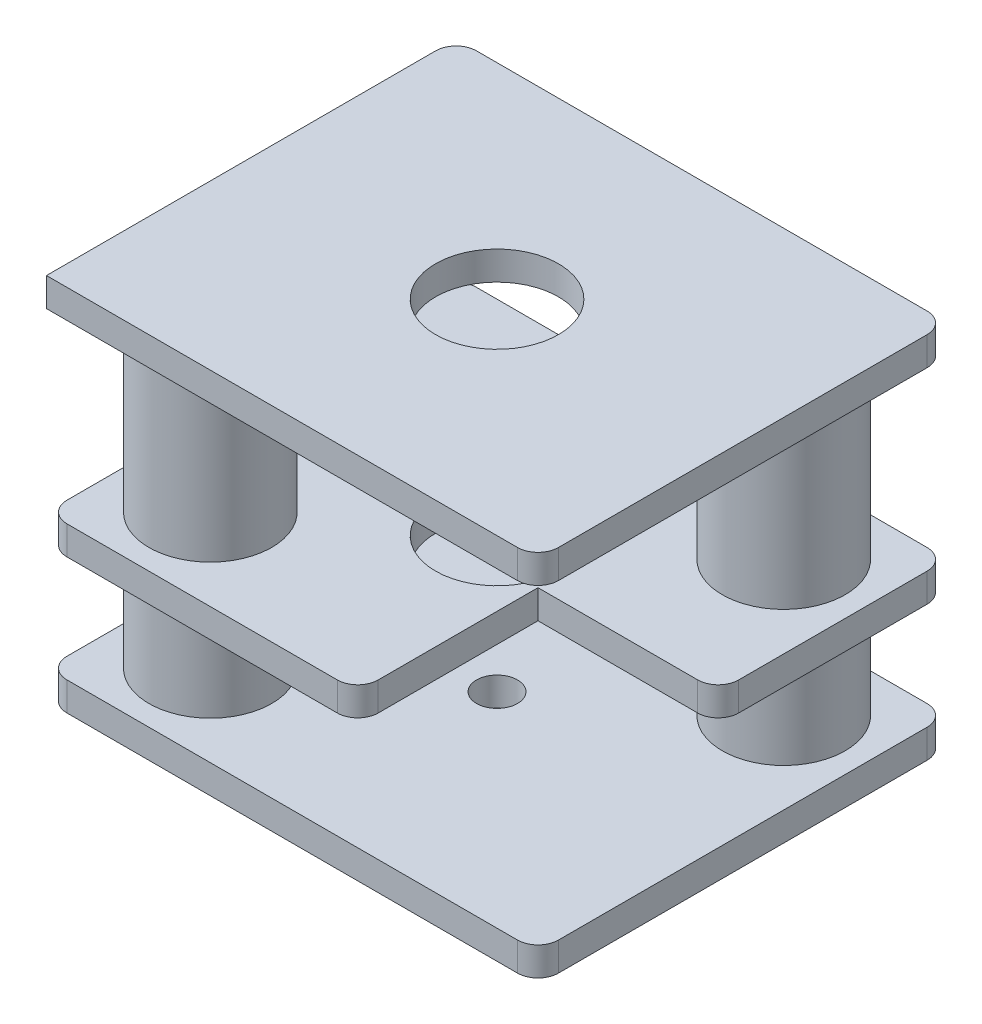
SolidWorks part; units mm, degrees
ref_plane "Alzado" through (0, 0, 0) normal (0, 0, 1) x (1, 0, 0)
ref_plane "Planta" through (0, 0, 0) normal (0, 1, 0) x (1, 0, 0)
ref_plane "Vista lateral" through (0, 0, 0) normal (1, 0, 0) x (0, 0, -1)
sketch "Croquis1" plane through (0, 0, 0) normal (0, 1, 0) x (1, 0, 0)
  line L1 (-6, 5) -> (6, 5)
  line L2 (-6, 5) -> (-6, -5)
  line L3 (-6, -5) -> (6, -5)
  line L4 (6, 5) -> (6, -5)
  line L5 (-6, 5) -> (6, -5) construction
  line L6 (-6, -5) -> (6, 5) construction
  circle A0 centre (0, 0) radius 0.5
  point P0 (0, 0)
  dimension "D3" = 1
  dimension "D1" = 12
  dimension "D2" = 10
extrude "Saliente-Extruir1" add sketch "Croquis1" along normal blind 0.7
sketch "Croquis2" plane through (0, 0.7, 0) normal (0, 1, 0) x (1, 0, 0)
  line L0 (6, -5) -> (6, 5) construction
  line L1 (-6, -5) -> (6, -5) construction
  line L3 (-6, 5) -> (-6, -5) construction
  line L4 (6, 5) -> (-6, 5) construction
  circle A0 centre (4, 3) radius 1.5
  circle A1 centre (-4, -3) radius 1.5
  dimension "D1" = 3
  dimension "D2" = 3
  dimension "D3" = 2
  dimension "D4" = 2
  dimension "D5" = 2
  dimension "D6" = 2
extrude "Saliente-Extruir2" add sketch "Croquis2" along normal blind 8.3
ref_plane "Plano1" through (0, 3.3, 0) normal (0, 1, 0) x (1, 0, 0)
sketch "Croquis3" plane through (0, 3.3, 0) normal (0, 1, 0) x (1, 0, 0)
  line L0 (6, -0.6) -> (1.6, -0.6)
  line L1 (1.6, -0.6) -> (1.6, -5)
  line L4 (6, -5) -> (6, 5)
  line L5 (6, 5) -> (-6, 5)
  line L6 (-6, 5) -> (-6, -5)
  line L7 (-6, -5) -> (6, -5)
  line L8 (6, -0.6) -> (6, 5)
  line L9 (6, 5) -> (-6, 5)
  line L10 (-6, 5) -> (-6, -5)
  line L11 (-6, -5) -> (1.6, -5)
  dimension "D2" = 4.4
  dimension "D3" = 4.4
  dimension "D1" = 0
extrude "Saliente-Extruir3" add sketch "Croquis3" along normal blind 0.7
ref_plane "Plano2" through (0, 8.3, 0) normal (0, 1, 0) x (1, 0, 0)
sketch "Croquis4" plane through (0, 8.3, 0) normal (0, 1, 0) x (1, 0, 0)
  line L0 (6, -0.6) -> (6, -5)
  line L1 (6, -5) -> (1.6, -5)
  line L6 (6, 5) -> (-6, 5)
  line L7 (-6, 5) -> (-6, -5)
  line L8 (-6, -5) -> (1.6, -5)
  line L9 (1.6, -5) -> (1.6, -0.6)
  line L10 (1.6, -0.6) -> (6, -0.6)
  line L11 (6, -0.6) -> (6, 5)
  line L12 (6, 5) -> (-6, 5)
  line L13 (-6, 5) -> (-6, -5)
  line L14 (-6, -5) -> (1.6, -5)
  line L17 (6, -0.6) -> (6, 5)
  dimension "D1" = 0
extrude "Saliente-Extruir4" add sketch "Croquis4" along normal blind 0.7
sketch "Croquis5" plane through (0, 9, 0) normal (0, 1, 0) x (1, 0, 0)
  circle A0 centre (0, 0) radius 1.5
  dimension "D1" = 3
extrude "Cortar-Extruir1" cut sketch "Croquis5" against normal up to surface (5.7 mm away) up to face at (4, 3.3, -1.5)
fillet "Redondeo1" radius 0.5 12 edges at (-6, 3.65, 5) (-6, 0.35, 5) (6, 8.65, 5) (1.6, 3.65, 5) (6, 3.65, 0.6) (6, 0.35, 5) (6, 0.35, -5) (6, 3.65, -5) (6, 8.65, -5) (-6, 0.35, -5) (-6, 3.65, -5) (-6, 8.65, -5)
